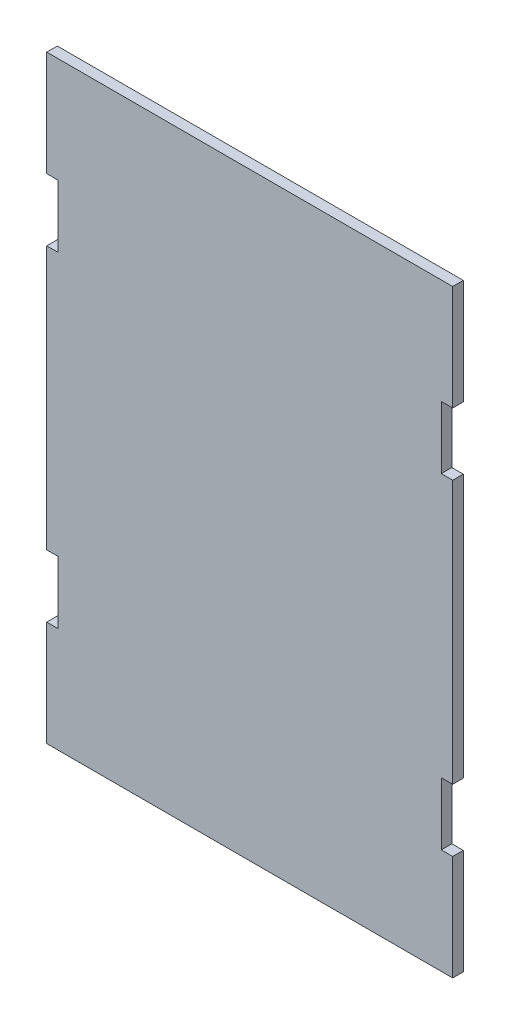
SolidWorks part; units mm, degrees
ref_plane "Спереди" through (0, 0, 0) normal (0, 0, 1) x (1, 0, 0)
ref_plane "Сверху" through (0, 0, 0) normal (0, 1, 0) x (1, 0, 0)
ref_plane "Справа" through (0, 0, 0) normal (1, 0, 0) x (0, 0, -1)
sketch "Эскиз1" plane through (0, 0, 0) normal (0, 0, 1) x (1, 0, 0)
  line L0 (-230.5, 220.5) -> (-217.5, 220.5)
  line L1 (230.5, -340) -> (-230.5, -340)
  line L2 (230.5, -340) -> (230.5, -220.5)
  line L3 (230.5, 340) -> (-230.5, 340)
  line L4 (-230.5, -340) -> (-230.5, -220.5)
  line L5 (230.5, -340) -> (-230.5, 340) construction
  line L6 (230.5, 340) -> (-230.5, -340) construction
  line L7 (-217.5, 220.5) -> (-217.5, 149.5)
  line L8 (-217.5, 149.5) -> (-230.5, 149.5)
  line L9 (-230.5, -149.5) -> (-217.5, -149.5)
  line L10 (-217.5, -149.5) -> (-217.5, -220.5)
  line L11 (-217.5, -220.5) -> (-230.5, -220.5)
  line L12 (230.5, -220.5) -> (217.5, -220.5)
  line L13 (217.5, -220.5) -> (217.5, -149.5)
  line L14 (217.5, -149.5) -> (230.5, -149.5)
  line L15 (230.5, 149.5) -> (217.5, 149.5)
  line L16 (217.5, 149.5) -> (217.5, 220.5)
  line L17 (217.5, 220.5) -> (230.5, 220.5)
  line L18 (-230.5, -149.5) -> (-230.5, 149.5)
  line L19 (-230.5, 220.5) -> (-230.5, 340)
  line L20 (230.5, 220.5) -> (230.5, 340)
  line L21 (230.5, -149.5) -> (230.5, 149.5)
  point P0 (0, 0)
  dimension "D3" = 71
  dimension "D1" = 461
  dimension "D2" = 680
  dimension "D4" = 71
  dimension "D5" = 13
  dimension "D6" = 13
  dimension "D7" = 71
  dimension "D8" = 71
  dimension "D9" = 13
  dimension "D10" = 13
  dimension "D11" = 119.5
  dimension "D12" = 119.5
  dimension "D13" = 119.5
  dimension "D14" = 119.5
extrude "Бобышка-Вытянуть1" add sketch "Эскиз1" along normal blind 12
